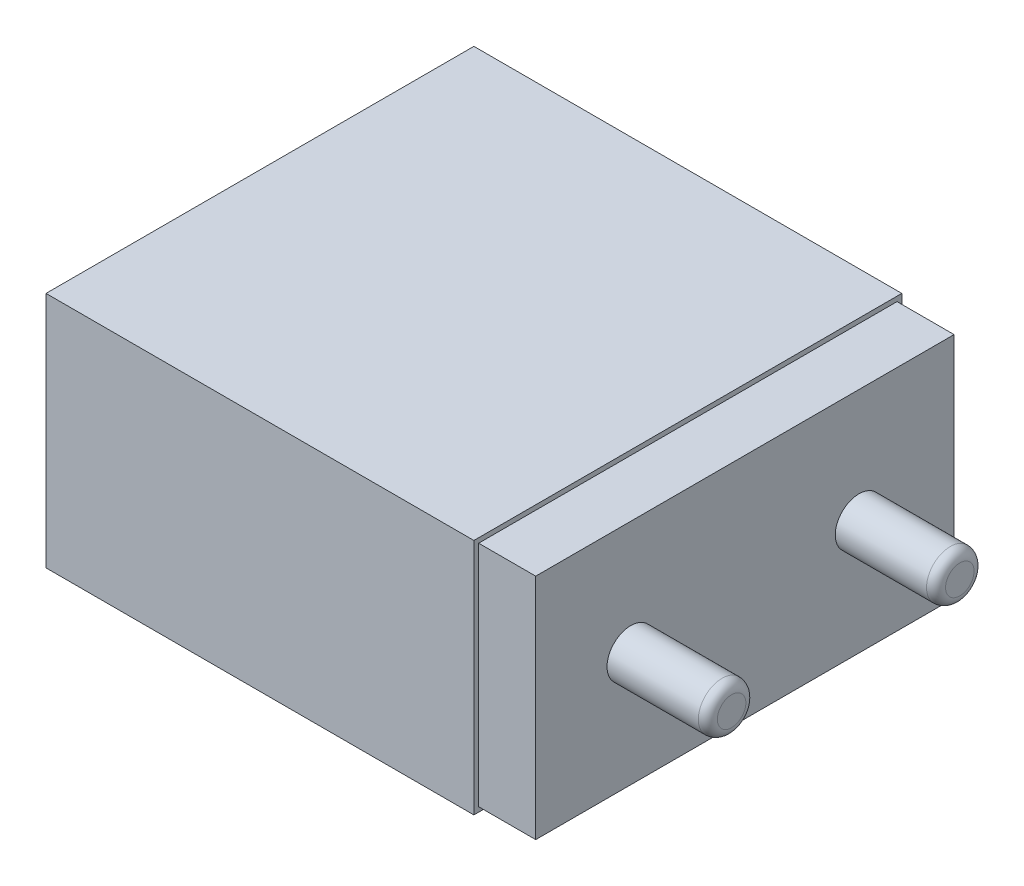
SolidWorks part; units mm, degrees
ref_plane "Front Plane" through (0, 0, 0) normal (0, 0, 1) x (1, 0, 0)
ref_plane "Top Plane" through (0, 0, 0) normal (0, 1, 0) x (1, 0, 0)
ref_plane "Right Plane" through (0, 0, 0) normal (1, 0, 0) x (0, 0, -1)
sketch "Sketch1" plane through (0, 0, 0) normal (0, 1, 0) x (1, 0, 0)
  line L1 (-25.5789, 29.2105) -> (19.4211, 29.2105)
  line L2 (-25.5789, 29.2105) -> (-25.5789, -15.7895)
  line L3 (-25.5789, -15.7895) -> (19.4211, -15.7895)
  line L4 (19.4211, 29.2105) -> (19.4211, -15.7895)
  dimension "D1" = 45
  dimension "D2" = 45
extrude "Boss-Extrude1" add sketch "Sketch1" along normal blind 25
sketch "Sketch2" plane through (19.4211, 0, 0) normal (1, 0, 0) x (0, 0, -1)
  line L0 (-15.7895, 25) -> (29.2105, 25) construction
  line L1 (-15.2895, 24.5) -> (28.7105, 24.5)
  line L2 (-15.2895, 24.5) -> (-15.2895, 0.5)
  line L3 (-15.2895, 0.5) -> (28.7105, 0.5)
  line L4 (28.7105, 24.5) -> (28.7105, 0.5)
  line L5 (-15.7895, 25) -> (-15.7895, 0) construction
  line L6 (29.2105, 25) -> (29.2105, 0) construction
  line L7 (-15.7895, 0) -> (29.2105, 0) construction
  dimension "D1" = 0.5
  dimension "D2" = 0.5
  dimension "D3" = 0.5
  dimension "D4" = 0.5
extrude "Boss-Extrude2" add sketch "Sketch2" along normal blind 6
sketch "Sketch3" plane through (25.4211, 0, 0) normal (1, 0, 0) x (0, 0, -1)
  line L0 (29.2105, 25) -> (29.2105, 0) construction
  line L1 (-15.7895, 25) -> (-15.7895, 0) construction
  line L4 (-15.7895, 0) -> (29.2105, 0) construction
  circle A0 centre (18.7105, 12.5) radius 2.5
  circle A1 centre (-5.2895, 12.5) radius 2.5
  dimension "D3" = 5
  dimension "D4" = 5
  dimension "D1" = 10.5
  dimension "D2" = 10.5
  dimension "D5" = 12.5
  dimension "D6" = 12.5
extrude "Boss-Extrude3" add sketch "Sketch3" along normal blind 10.6
fillet "Fillet12" radius 1 1 edges at (36.0211, 12.5, 2.7895)
fillet "Fillet13" radius 1 1 edges at (36.0211, 12.5, -21.2105)
sketch "Sketch4" plane through (-25.5789, 0, 0) normal (-1, 0, 0) x (0, 0, 1)
  line L0 (-29.2105, 25) -> (-29.2105, 0) construction
  line L1 (-24.2105, 18.4531) -> (-19.2105, 18.4531)
  line L2 (-24.2105, 18.4531) -> (-24.2105, 7.9531)
  line L3 (-24.2105, 7.9531) -> (-19.2105, 7.9531)
  line L4 (-19.2105, 18.4531) -> (-19.2105, 7.9531)
  line L6 (-14.2105, 18.4531) -> (-9.2105, 18.4531)
  line L7 (-14.2105, 18.4531) -> (-14.2105, 7.9531)
  line L8 (-14.2105, 7.9531) -> (-9.2105, 7.9531)
  line L9 (-9.2105, 18.4531) -> (-9.2105, 7.9531)
  dimension "D1" = 5
  dimension "D2" = 10.5
  dimension "D3" = 5
  dimension "D4" = 5
  dimension "D5" = 5
extrude "Cut-Extrude1" cut sketch "Sketch4" against normal blind 10.5
sketch "Sketch5" plane through (-25.5789, 0, 0) normal (-1, 0, 0) x (0, 0, 1)
  line L0 (15.7895, 25) -> (15.7895, 0) construction
  line L1 (-4.2105, 18.4531) -> (10.7895, 18.4531)
  line L2 (-4.2105, 18.4531) -> (-4.2105, 7.9531)
  line L3 (-4.2105, 7.9531) -> (10.7895, 7.9531)
  line L4 (10.7895, 18.4531) -> (10.7895, 7.9531)
  dimension "D1" = 15
  dimension "D2" = 5
extrude "Boss-Extrude4" add sketch "Sketch5" along normal blind 0.5
fillet "Fillet14" radius 0.1 4 edges at (-26.0789, 13.2031, 10.7895) (-26.0789, 18.4531, 3.2895) (-26.0789, 7.9531, 3.2895) (-26.0789, 13.2031, -4.2105)
